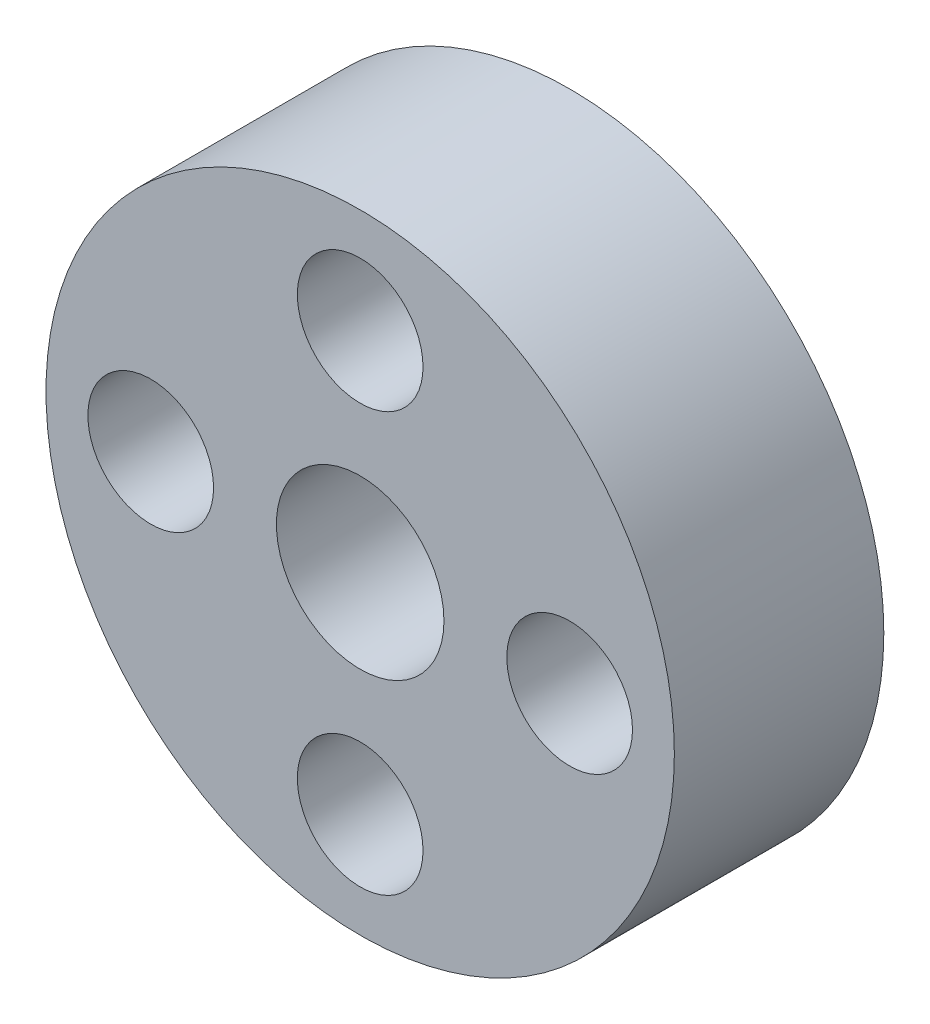
SolidWorks part; units mm, degrees
ref_plane "Front Plane" through (0, 0, 0) normal (0, 0, 1) x (1, 0, 0)
ref_plane "Top Plane" through (0, 0, 0) normal (0, 1, 0) x (1, 0, 0)
ref_plane "Right Plane" through (0, 0, 0) normal (1, 0, 0) x (0, 0, -1)
sketch "Sketch1" plane through (0, 0, 0) normal (0, 0, 1) x (1, 0, 0)
  line L0 (0, 15) -> (0, -15) construction
  line L1 (-15, 0) -> (15, 0) construction
  circle A0 centre (0, 0) radius 15
  circle A1 centre (0, 0) radius 10 construction
  circle A2 centre (0, 10) radius 3
  circle A3 centre (10, 0) radius 3
  circle A4 centre (0, -10) radius 3
  circle A5 centre (-10, 0) radius 3
  circle A6 centre (0, 0) radius 4
  dimension "D1" = 8
  dimension "D2" = 30
  dimension "D3" = 20
  dimension "D6" = 10
  dimension "D7" = 10
  dimension "D9" = 6
  dimension "D5" = 10
  dimension "D11" = 0
extrude "Boss-Extrude1" add sketch "Sketch1" along normal blind 10
